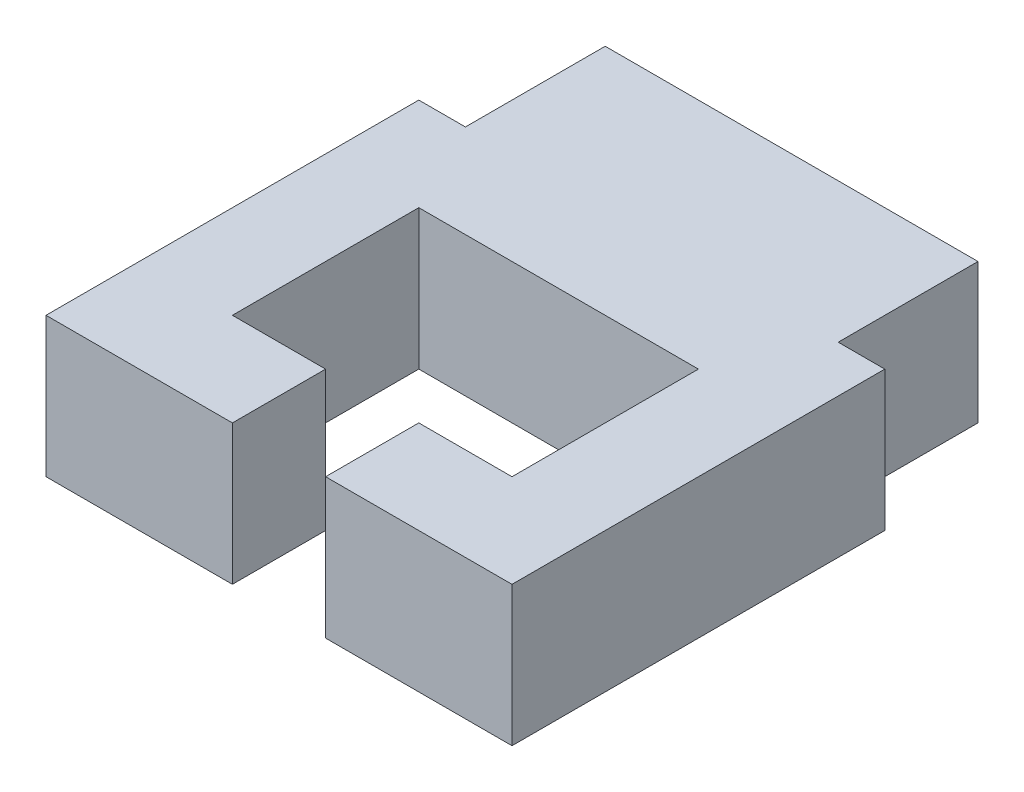
SolidWorks part; units mm, degrees
ref_plane "Front Plane" through (0, 0, 0) normal (0, 0, 1) x (1, 0, 0)
ref_plane "Top Plane" through (0, 0, 0) normal (0, 1, 0) x (1, 0, 0)
ref_plane "Right Plane" through (0, 0, 0) normal (1, 0, 0) x (0, 0, -1)
sketch "Sketch4" plane through (0, 0, 0) normal (0, 0, 1) x (1, 0, 0)
  line L1 (-117.4236, 37.2152) -> (-107.4236, 37.2152)
  line L2 (-117.4236, 37.2152) -> (-117.4236, 34.2152)
  line L3 (-117.4236, 34.2152) -> (-107.4236, 34.2152)
  line L4 (-107.4236, 37.2152) -> (-107.4236, 34.2152)
extrude "Boss-Extrude2" add sketch "Sketch4" along normal blind 2
sketch "Sketch5" plane through (0, 0, 0) normal (0, 0, -1) x (-1, 0, 0)
  line L0 (112.4236, 37.2152) -> (112.4236, 34.2152) construction
  line L1 (107.4236, 37.2152) -> (117.4236, 37.2152) construction
  line L2 (117.4236, 34.2152) -> (107.4236, 34.2152) construction
  line L3 (112.4236, 34.2152) -> (108.4236, 34.2152)
  line L4 (108.4236, 34.2152) -> (108.4236, 37.2152)
  line L5 (108.4236, 37.2152) -> (116.4236, 37.2152)
  line L6 (116.4236, 37.2152) -> (116.4236, 34.2152)
  line L7 (116.4236, 34.2152) -> (108.4236, 34.2152)
  line M2 (117.4236, 37.2152) -> (107.4236, 37.2152)
  line M4 (107.4236, 34.2152) -> (117.4236, 34.2152)
extrude "Boss-Extrude3" add sketch "Sketch5" along normal blind 3 contours L0 L6 M2 M4 | L0 L5 L4 M4
sketch "Sketch6" plane through (0, 0, 2) normal (0, 0, 1) x (1, 0, 0)
  line L0 (-107.4236, 37.2152) -> (-109.4236, 37.2152)
  line L1 (-107.4236, 37.2152) -> (-117.4236, 37.2152) construction
  line L2 (-109.4236, 37.2152) -> (-109.4236, 34.2152)
  line L3 (-117.4236, 34.2152) -> (-107.4236, 34.2152) construction
  line L4 (-109.4236, 34.2152) -> (-107.4236, 34.2152)
  line L5 (-107.4236, 34.2152) -> (-107.4236, 37.2152)
  line L6 (-117.4236, 37.2152) -> (-115.4236, 37.2152)
  line L7 (-115.4236, 37.2152) -> (-115.4236, 34.2152)
  line L8 (-115.4236, 34.2152) -> (-117.4236, 34.2152)
  line L9 (-117.4236, 34.2152) -> (-117.4236, 37.2152)
extrude "Boss-Extrude4" add sketch "Sketch6" along normal blind 6
sketch "Sketch7" plane through (-115.4236, 0, 0) normal (1, 0, 0) x (0, 0, -1)
  line L0 (-8, 37.2152) -> (-6, 37.2152)
  line L1 (-8, 37.2152) -> (-2, 37.2152) construction
  line L2 (-6, 37.2152) -> (-6, 34.2152)
  line L3 (-8, 34.2152) -> (-2, 34.2152) construction
  line L4 (-6, 34.2152) -> (-8, 34.2152)
  line L5 (-8, 34.2152) -> (-8, 37.2152)
extrude "Boss-Extrude5" add sketch "Sketch7" along normal blind 2
sketch "Sketch8" plane through (-109.4236, 0, 0) normal (-1, 0, 0) x (0, 0, 1)
  line L0 (8, 34.2152) -> (2, 34.2152) construction
  line L1 (8, 37.2152) -> (6, 37.2152)
  line L2 (8, 37.2152) -> (8, 34.2152)
  line L3 (8, 34.2152) -> (6, 34.2152)
  line L4 (6, 37.2152) -> (6, 34.2152)
extrude "Boss-Extrude6" add sketch "Sketch8" along normal blind 2
